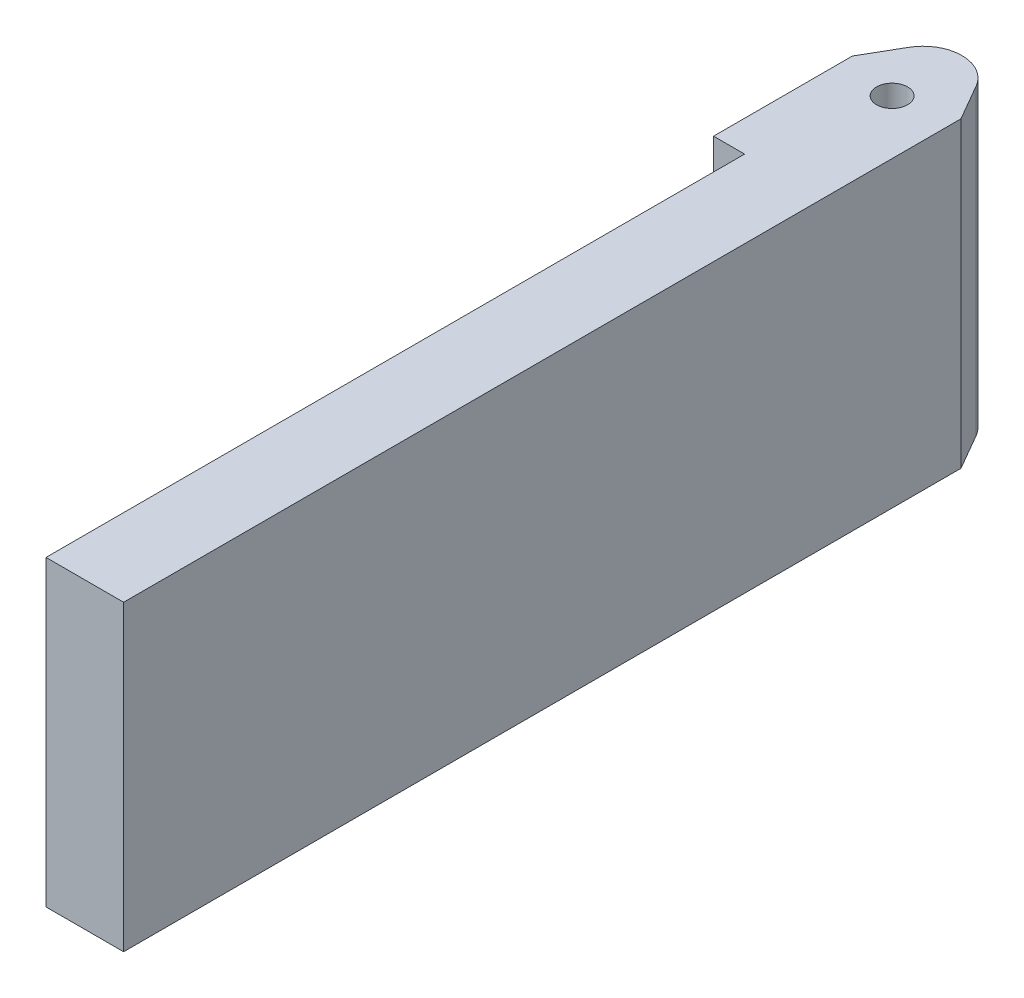
SolidWorks part; units mm, degrees
ref_plane "Front Plane" through (0, 0, 0) normal (0, 0, 1) x (1, 0, 0)
ref_plane "Top Plane" through (0, 0, 0) normal (0, 1, 0) x (1, 0, 0)
ref_plane "Right Plane" through (0, 0, 0) normal (1, 0, 0) x (0, 0, -1)
sketch "Sketch1" plane through (0, 0, 0) normal (0, 1, 0) x (1, 0, 0)
  line L1 (-15, -60) -> (15, -60)
  line L2 (-15, -60) -> (-15, 60)
  line L3 (-15, 60) -> (15, 60)
  line L4 (15, -60) -> (15, 60)
  line L5 (-15, -60) -> (15, 60) construction
  line L6 (-15, 60) -> (15, -60) construction
  point P0 (0, 0)
  dimension "D1" = 30
  dimension "D2" = 120
extrude "Boss-Extrude1" add sketch "Sketch1" along normal blind 39
sketch "Sketch2" plane through (0, 39, 0) normal (0, 1, 0) x (1, 0, 0)
  line L0 (0, 60) -> (-15, 34.0192)
  line L1 (15, 60) -> (-15, 60) construction
  line L2 (-15, 60) -> (-15, -60) construction
  line L3 (-15, 34.0192) -> (-15, -60)
  line L4 (-15, -60) -> (15, -60)
  line L5 (15, -60) -> (15, 34.0192)
  line L6 (15, -60) -> (15, 60) construction
  line L7 (15, 34.0192) -> (0, 60)
  dimension "D1" = 60
  dimension "D2" = 0
extrude "Cut-Extrude2" cut sketch "Sketch2" against normal through all flip side to cut
fillet "Fillet1" radius 5 1 edges at (0, 19.5, -60)
sketch "Sketch3" plane through (0, 39, 0) normal (0, 1, 0) x (1, 0, 0)
  line L0 (-15, 34.0192) -> (-15, -60)
  line L1 (-15, -60) -> (-7, -60)
  line L2 (-15, -60) -> (15, -60) construction
  line L3 (-7, -60) -> (-7, 47.8756)
  line L4 (-4.3301, 52.5) -> (-15, 34.0192) construction
  line L5 (-7, 47.8756) -> (-15, 34.0192)
  line L6 (7, 47.8756) -> (7, -60)
  line L7 (15, 34.0192) -> (4.3301, 52.5) construction
  line L8 (7, -60) -> (15, -60)
  line L9 (15, -60) -> (15, 34.0192)
  line L10 (15, 34.0192) -> (7, 47.8756)
  dimension "D1" = 8
  dimension "D2" = 8
extrude "Cut-Extrude3" cut sketch "Sketch3" against normal through all
sketch "Sketch4" plane through (0, 39, 0) normal (0, 1, 0) x (1, 0, 0)
  line L0 (-7, -60) -> (-7, 47.8756) construction
  line L1 (-7, 30) -> (-3, 30)
  line L2 (-7, 30) -> (-7, -60)
  line L3 (-7, -60) -> (-3, -60)
  line L4 (-3, 30) -> (-3, -60)
  line L5 (-7, -60) -> (7, -60) construction
  dimension "D1" = 90
  dimension "D2" = 4
extrude "Cut-Extrude4" cut sketch "Sketch4" against normal through all
sketch "Sketch5" plane through (0, 39, 0) normal (0, 1, 0) x (1, 0, 0)
  circle A0 centre (0, 46) radius 2
  arc A1 (4.3301, 52.5) -> (-4.3301, 52.5) centre (0, 50) ccw construction
  dimension "D1" = 4
extrude "Cut-Extrude5" cut sketch "Sketch5" against normal through all
